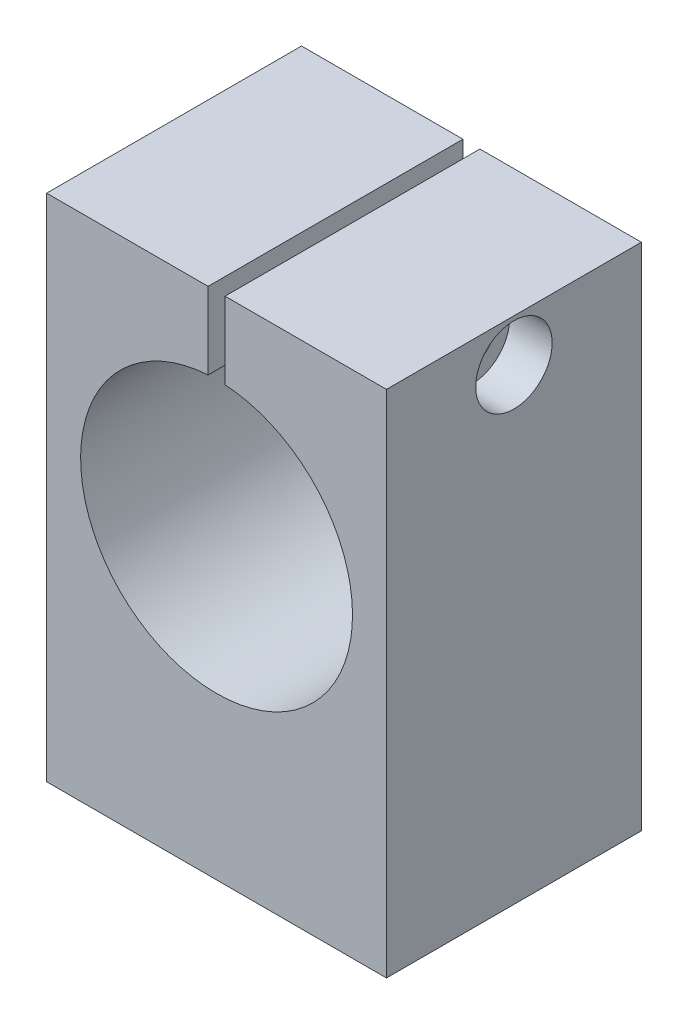
SolidWorks part; units mm, degrees
material "AISI 1020"
ref_plane "Alzado" through (0, 0, 0) normal (0, 0, 1) x (1, 0, 0)
ref_plane "Planta" through (0, 0, 0) normal (0, 1, 0) x (1, 0, 0)
ref_plane "Vista lateral" through (0, 0, 0) normal (1, 0, 0) x (0, 0, -1)
sketch "Croquis1" plane through (0, 0, 0) normal (0, 0, 1) x (1, 0, 0)
  line L0 (0, 55.7337) -> (0, -30) construction
  line L1 (-20, -30) -> (20, -30)
  line L2 (-20, -30) -> (-20, 30)
  line L3 (-20, 30) -> (-1, 30)
  line L4 (20, -30) -> (20, 30)
  line L5 (-20, -30) -> (20, 30) construction
  line L6 (-20, 30) -> (20, -30) construction
  line L7 (-20, 5) -> (20, 5) construction
  line L8 (1, 30) -> (20, 30)
  line L10 (-1, 20.9687) -> (-1, 30)
  line L12 (1, 20.9687) -> (1, 30)
  arc A0 (-1, 20.9687) -> (1, 20.9687) centre (0, 5) ccw
  point P0 (0, 0)
  dimension "D4" = 32
  dimension "D1" = 40
  dimension "D2" = 60
  dimension "D3" = 25
  dimension "D5" = 1
  dimension "D6" = 1
  dimension "D7" = 19
extrude "Saliente-Extruir1" add sketch "Croquis1" along normal blind 30
sketch "Croquis2" plane through (0, -30, 0) normal (0, -1, 0) x (1, 0, 0)
  line L0 (20, 30) -> (20, 0) construction
  line L1 (-20, 30) -> (20, 30) construction
  line L2 (-20, 0) -> (20, 0) construction
  line L3 (-20, 30) -> (-20, 0) construction
  point P0 (-15, 25)
  point P1 (15, 25)
  point P2 (15, 5)
  point P3 (-15, 5)
  dimension "D1" = 5
  dimension "D2" = 5
  dimension "D3" = 5
  dimension "D4" = 5
hole_wizard "Taladro roscado M4x0.71" positions "Croquis3" profile "Croquis4" tap size "M4x0.7" standard "Ansi Metric"
sketch "Croquis3" plane through (0, -30, 0) normal (0, -1, 0) x (-1, 0, 0)
  point P0 (-15, -5)
  point P3 (-15, -25)
  point P6 (15, -5)
  point P9 (15, -25)
sketch "Croquis4" plane through (15, -30, 5) normal (1, 0, 0) x (0, 0, -1)
  line L0 (0, 0) -> (0, 15.9914)
  line L1 (0, 15.9914) -> (1.65, 15)
  line L2 (1.65, 15) -> (1.65, 0)
  line L5 (1.65, 0) -> (0, 0)
  line L10 (0, 15.9914) -> (-1.65, 15) construction
  line L11 (0, -6.35) -> (0, 107.95) construction
  dimension "Diámetro de perforador para roscar" = 3.3
  dimension "Profundidad de perforador para roscar" = 15
  dimension "Ángulo de perforador" = 118
cosmetic thread "Rosca de taladro1" parameters "D1"=8, "D2"=4
cosmetic thread "Rosca de taladro2" parameters "D1"=8, "D2"=4
cosmetic thread "Rosca de taladro3" parameters "D1"=8, "D2"=4
cosmetic thread "Rosca de taladro4" parameters "D1"=8, "D2"=4
sketch "Croquis5" plane through (20, 0, 0) normal (1, 0, 0) x (0, 0, -1)
  line L0 (-15, 25) -> (-15, 30) construction
  line L1 (-30, 30) -> (0, 30) construction
  point P0 (-15, 25)
  dimension "D1" = 5
hole_wizard "Refrentado para tornillo tapón con cabeza de clavija de M52" positions "Croquis6" profile "Croquis8" counterbore size "M5" standard "Ansi Metric" end condition through all
sketch "Croquis6" plane through (20, 0, 0) normal (1, 0, 0) x (0, 0, -1)
  point P0 (-15, 25)
sketch "Croquis8" plane through (20, 25, 15) normal (0, 1, 0) x (0, 0, -1)
  line L0 (0, 0) -> (0, 40)
  line L1 (0, 40) -> (2.65, 40)
  line L3 (2.65, 40) -> (2.65, 5)
  line L4 (2.65, 5) -> (4.5, 5)
  line L5 (4.5, 5) -> (4.5, 0)
  line L7 (4.5, 0) -> (0, 0)
  line L11 (0, -6.35) -> (0, 107.95) construction
  dimension "Diámetro de taladro hasta el siguiente" = 5.3
  dimension "Profundidad de taladro hasta el siguiente" = 40
  dimension "Diámetro de refrentado" = 9
  dimension "Profundidad de refrentado" = 5
sketch "Croquis9" plane through (-20, 0, 0) normal (-1, 0, 0) x (0, 0, 1)
  circle A0 centre (15, 25) radius 2.65 construction
  circle A1 centre (15, 25) radius 2.65
extrude "Saliente-Extruir2" add sketch "Croquis9" against normal up to surface (19 mm away) up to face at (-1, 22.35, 15)
sketch "Croquis10" plane through (-20, 0, 0) normal (-1, 0, 0) x (0, 0, 1)
  point P0 (15, 25)
hole_wizard "Taladro roscado M5x0.82" positions "Croquis17" profile "Croquis18" tap size "M5x0.8" standard "Ansi Metric" end condition up to next
sketch "Croquis17" plane through (-20, 0, 0) normal (-1, 0, 0) x (0, 0, 1)
  point P0 (15, 25)
sketch "Croquis18" plane through (-20, 25, 15) normal (0, 1, 0) x (0, 0, 1)
  line L0 (0, 0) -> (0, 19)
  line L1 (0, 19) -> (2.25, 19)
  line L2 (2.25, 19) -> (2.25, 0)
  line L5 (2.25, 0) -> (0, 0)
  line L11 (0, -6.35) -> (0, 107.95) construction
  dimension "Diámetro de perforador para roscar hasta el siguiente" = 4.5
  dimension "Profundidad de perforador para roscar hasta el siguiente" = 19
cosmetic thread "Rosca de taladro6" parameters "D2"=5
